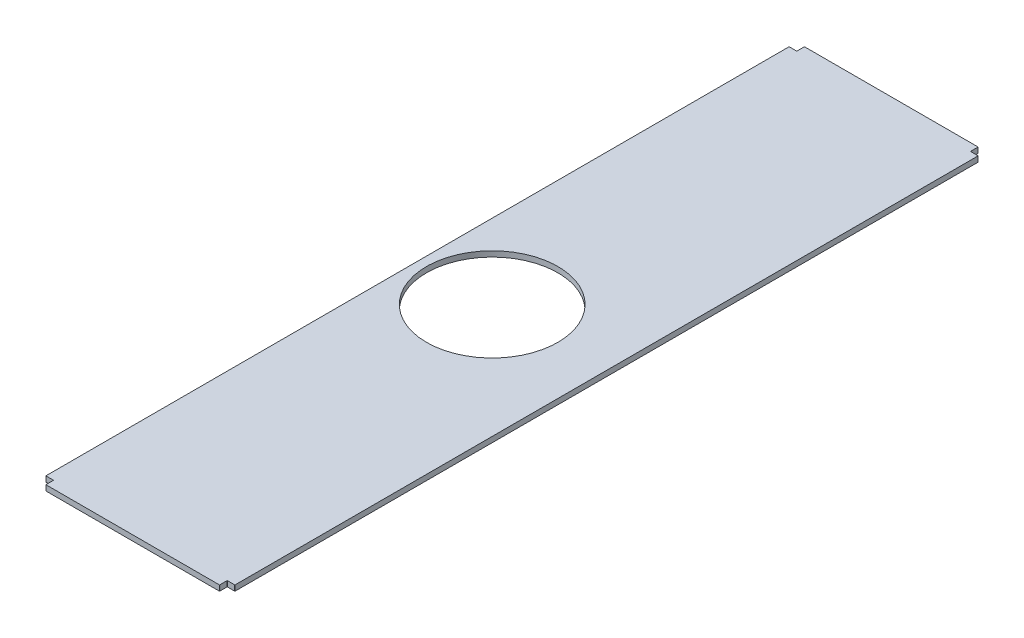
SolidWorks part; units mm, degrees
material "PE High Density"
ref_plane "Front Plane" through (0, 0, 0) normal (0, 0, 1) x (1, 0, 0)
ref_plane "Top Plane" through (0, 0, 0) normal (0, 1, 0) x (1, 0, 0)
ref_plane "Right Plane" through (0, 0, 0) normal (1, 0, 0) x (0, 0, -1)
sketch "Sketch1" plane through (0, 0, 0) normal (0, 1, 0) x (1, 0, 0)
  line L20 (219.202, 0) -> (0, 0)
  line L21 (0, 0) -> (0, 879.7036)
  line L23 (219.202, 0) -> (219.202, 879.7036)
  line L25 (0, 879.7036) -> (219.202, 879.7036)
  point P0 (0, 0)
  dimension "D1" = 879.7036
  dimension "D2" = 219.202
extrude "Boss-Extrude1" add sketch "Sketch1" along normal blind 6.35
sketch "Sketch4" plane through (0, 6.35, 0) normal (0, 1, 0) x (1, 0, 0)
  line L1 (0, 0) -> (8.89, 0)
  line L2 (0, 0) -> (0, 8.89)
  line L3 (0, 8.89) -> (8.89, 8.89)
  line L4 (8.89, 0) -> (8.89, 8.89)
  line L5 (219.202, 0) -> (210.312, 0)
  line L6 (219.202, 0) -> (219.202, 8.89)
  line L7 (219.202, 8.89) -> (210.312, 8.89)
  line L8 (210.312, 0) -> (210.312, 8.89)
  line L9 (219.202, 879.7036) -> (210.312, 879.7036)
  line L10 (219.202, 879.7036) -> (219.202, 870.8136)
  line L11 (219.202, 870.8136) -> (210.312, 870.8136)
  line L12 (210.312, 879.7036) -> (210.312, 870.8136)
  line L13 (0, 879.7036) -> (8.89, 879.7036)
  line L14 (0, 879.7036) -> (0, 870.8136)
  line L15 (0, 870.8136) -> (8.89, 870.8136)
  line L16 (8.89, 879.7036) -> (8.89, 870.8136)
  circle A0 centre (86.6394, 439.8518) radius 76.2
  dimension "D1" = 152.4
  dimension "D2" = 86.6394
  dimension "D3" = 439.8518
  dimension "D4" = 8.89
extrude "Cut-Extrude3" cut sketch "Sketch4" against normal through all
fillet "Fillet1" radius 0.254 12 edges at (210.312, 3.175, -879.7036) (210.312, 3.175, -870.8136) (219.202, 3.175, -870.8136) (0, 3.175, -870.8136) (8.89, 3.175, -870.8136) (8.89, 3.175, -879.7036) (8.89, 3.175, 0) (8.89, 3.175, -8.89) (0, 3.175, -8.89) (219.202, 3.175, -8.89) (210.312, 3.175, -8.89) (210.312, 3.175, 0)
